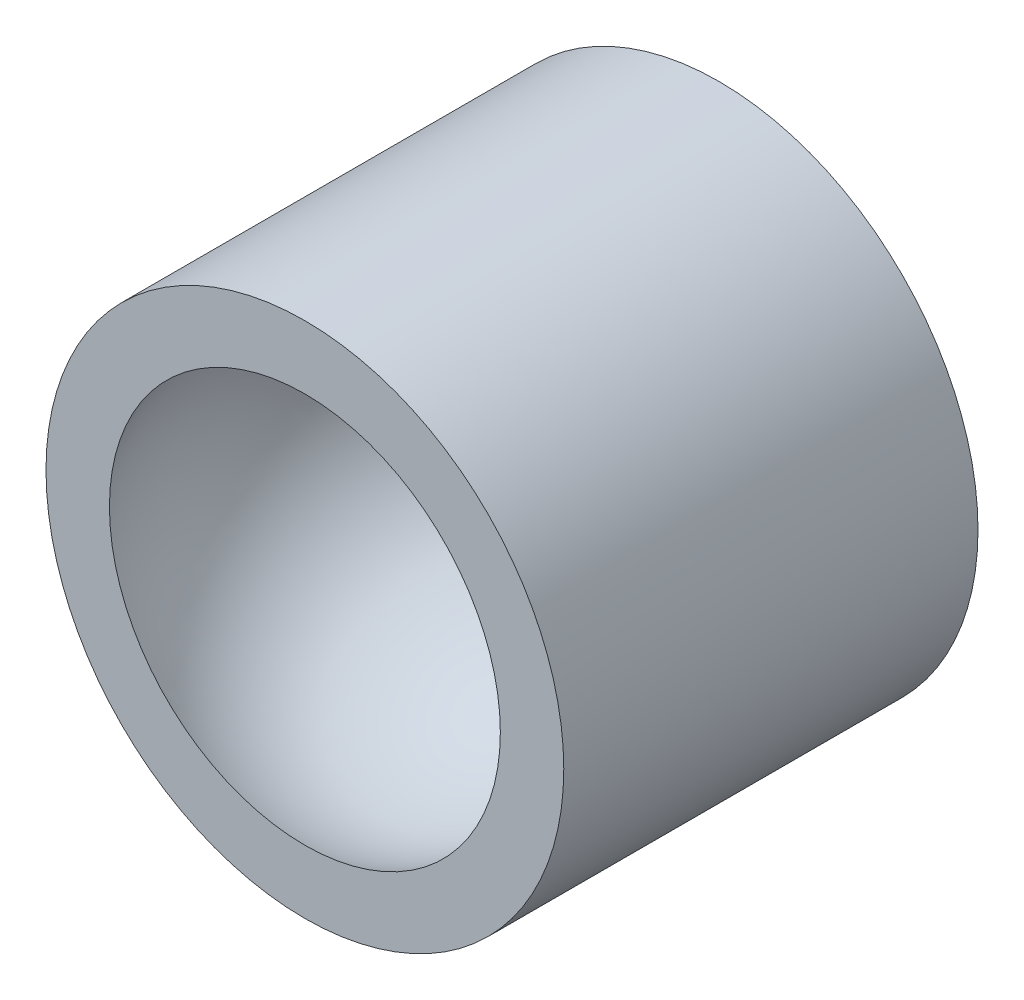
SolidWorks part; units mm, degrees
ref_plane "정면" through (0, 0, 0) normal (0, 0, 1) x (1, 0, 0)
ref_plane "윗면" through (0, 0, 0) normal (0, 1, 0) x (1, 0, 0)
ref_plane "우측면" through (0, 0, 0) normal (1, 0, 0) x (0, 0, -1)
sketch "스케치1" plane through (0, 0, 0) normal (0, 0, 1) x (1, 0, 0)
  circle A0 centre (0, 0) radius 12.5
extrude "보스-돌출2" add sketch "스케치1" along normal blind 35
sketch "스케치3" plane through (0, 0, 0) normal (0, 1, 0) x (1, 0, 0)
  line L0 (0, -35) -> (0, -31) construction
  line L1 (-12.5, -35) -> (12.5, -35) construction
  line L2 (0, -21) -> (0, -41)
  arc A0 (0, -21) -> (0, -41) centre (0, -31) ccw
revolve "컷-회전1" cut sketch "스케치3" angle 360 about L0
sketch "스케치4" plane through (0, 0, 0) normal (0, 0, -1) x (-1, 0, 0)
  circle A0 centre (0, 0) radius 14.6245
extrude "컷-돌출1" cut sketch "스케치4" against normal blind 15
sketch "스케치5" plane through (0, 0, 0) normal (0, 1, 0) x (1, 0, 0)
  line L0 (0, -35) -> (0, -31) construction
  line L1 (-12.5, -35) -> (12.5, -35) construction
  line L2 (0, -20.75) -> (0, -41.25)
  arc A0 (0, -20.75) -> (0, -41.25) centre (0, -31) ccw
revolve "컷-회전2" cut sketch "스케치5" angle 360 about L0
